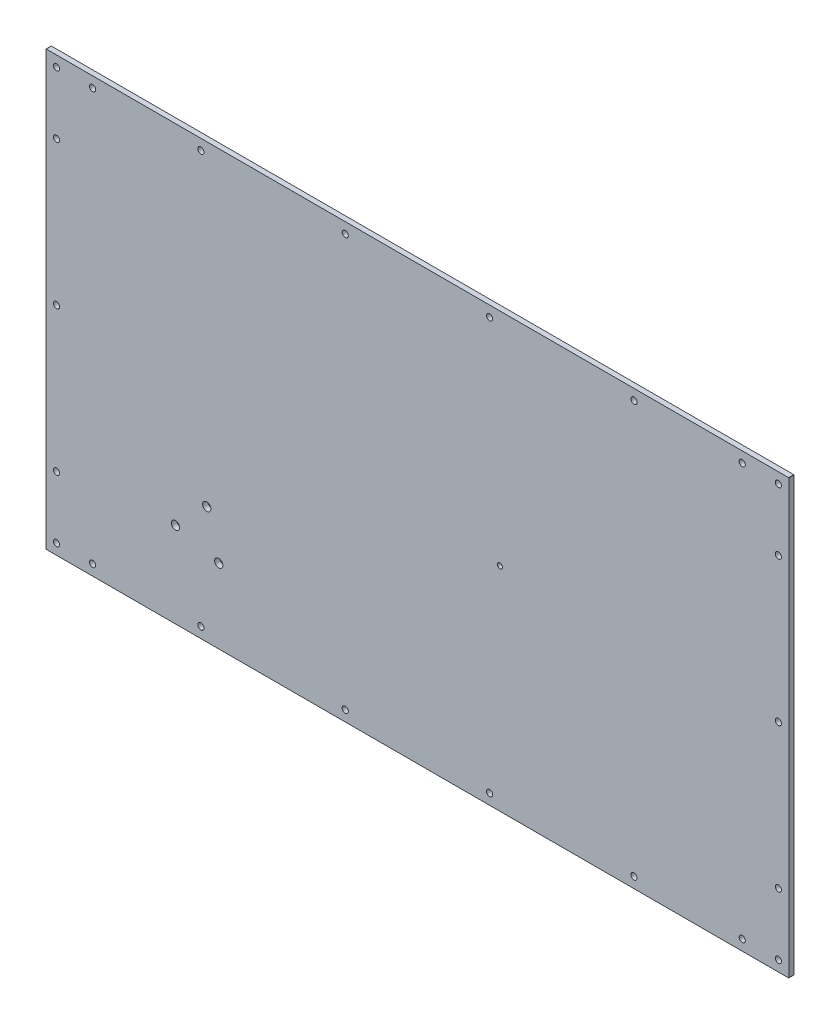
SolidWorks part; units mm, degrees
material "PE High Density"
ref_plane "Front Plane" through (0, 0, 0) normal (0, 0, 1) x (1, 0, 0)
ref_plane "Top Plane" through (0, 0, 0) normal (0, 1, 0) x (1, 0, 0)
ref_plane "Right Plane" through (0, 0, 0) normal (1, 0, 0) x (0, 0, -1)
sketch "Sketch1" plane through (0, 0, 0) normal (0, 0, 1) x (1, 0, 0)
  line L37 (-25.1555, 18.7938) -> (889.2445, 18.7938)
  line L40 (-25.1555, -514.6062) -> (889.2445, -514.6062)
  line L41 (889.2445, 18.7938) -> (889.2445, -514.6062)
  line L42 (-25.1555, 18.7938) -> (-25.1555, -514.6062)
  point P0 (0, 0)
  dimension "D1" = 533.4
  dimension "D2" = 914.4
extrude "Boss-Extrude1" add sketch "Sketch1" along normal blind 6.35
fillet "Fillet1" radius 0.254 4 edges at (889.2445, 18.7938, 3.175) (889.2445, -514.6062, 3.175) (-25.1555, -514.6062, 3.175) (-25.1555, 18.7938, 3.175)
sketch "Sketch2" plane through (0, 0, 0) normal (0, 0, -1) x (-1, 0, 0)
  line L0 (24.9015, -514.6062) -> (-888.9905, -514.6062) construction
  line L1 (25.1555, 18.5398) -> (25.1555, -514.3522) construction
  circle A0 centre (-187.4815, -423.1662) radius 5.08
  circle A1 centre (-134.2295, -409.44) radius 5.08
  circle A2 centre (-172.7427, -370.1855) radius 5.08
  dimension "D1" = 10.16
  dimension "D2" = 39.2546
  dimension "D3" = 13.7261
  dimension "D4" = 38.5132
  dimension "D5" = 14.7388
  dimension "D6" = 91.44
  dimension "D7" = 159.385
extrude "Cut-Extrude1" cut sketch "Sketch2" against normal through all
sketch "Sketch3" plane through (0, 0, 6.35) normal (0, 0, 1) x (1, 0, 0)
  line L0 (876.3445, -247.9062) -> (698.6245, -247.9062) construction
  line L1 (876.3445, 5.7128) -> (-12.2555, 5.7128) construction
  line L2 (876.3445, 5.7128) -> (876.3445, -501.5252) construction
  line L3 (876.3445, -501.5252) -> (-12.2555, -501.5252) construction
  line L4 (-12.2555, 5.7128) -> (-12.2555, -501.5252) construction
  line L5 (698.6245, -247.9062) -> (520.9045, -247.9062) construction
  line L6 (520.9045, -247.9062) -> (343.1845, -247.9062) construction
  line L7 (343.1845, -247.9062) -> (165.4645, -247.9062) construction
  line L8 (165.4645, -247.9062) -> (-12.2555, -247.9062) construction
  line L9 (-25.1555, 18.5398) -> (-25.1555, -514.3522) construction
  line L10 (888.9905, 18.7938) -> (-24.9015, 18.7938) construction
  circle A0 centre (876.3445, 5.7128) radius 3.81
  circle A1 centre (876.3445, -247.9062) radius 3.81
  circle A2 centre (876.3445, -501.5252) radius 3.81
  circle A3 centre (-12.2555, 5.7128) radius 3.81
  circle A4 centre (-12.2555, -247.9062) radius 3.81
  circle A5 centre (-12.2555, -501.5252) radius 3.81
  circle A6 centre (698.6245, 5.7128) radius 3.81
  circle A7 centre (520.9045, 5.7128) radius 3.81
  circle A8 centre (343.1845, 5.7128) radius 3.81
  circle A9 centre (165.4645, 5.7128) radius 3.81
  circle A10 centre (698.6245, -501.5252) radius 3.81
  circle A11 centre (520.9045, -501.5252) radius 3.81
  circle A12 centre (343.1845, -501.5252) radius 3.81
  circle A13 centre (165.4645, -501.5252) radius 3.81
  circle A14 centre (831.8945, 5.7128) radius 3.81
  circle A15 centre (876.3445, -70.4872) radius 3.81
  circle A16 centre (876.3445, -425.3252) radius 3.81
  circle A17 centre (831.8945, -501.5252) radius 3.81
  circle A18 centre (32.1945, -501.5252) radius 3.81
  circle A19 centre (-12.2555, -425.3252) radius 3.81
  circle A20 centre (-12.2555, -70.4872) radius 3.81
  circle A21 centre (32.1945, 5.7128) radius 3.81
  point P47 (-25.1555, -247.9062)
  point P51 (432.0445, 18.7938)
  point P54 (432.0445, -247.9062)
  dimension "D3" = 7.62
  dimension "D4" = 888.6
  dimension "D5" = 507.238
  dimension "D6" = 44.45
  dimension "D7" = 76.2
  dimension "D8" = 44.45
  dimension "D9" = 76.2
extrude "Cut-Extrude2" cut sketch "Sketch3" against normal through all
sketch "Sketch4" plane through (0, 0, 6.35) normal (0, 0, 1) x (1, 0, 0)
  line L0 (889.2445, -514.3522) -> (889.2445, 18.5398) construction
  line L1 (-24.9015, -514.6062) -> (888.9905, -514.6062) construction
  circle A0 centre (533.6445, -252.9862) radius 3.175
  dimension "D3" = 6.35
  dimension "D1" = 355.6
  dimension "D2" = 261.62
extrude "Cut-Extrude3" cut sketch "Sketch4" against normal through all
